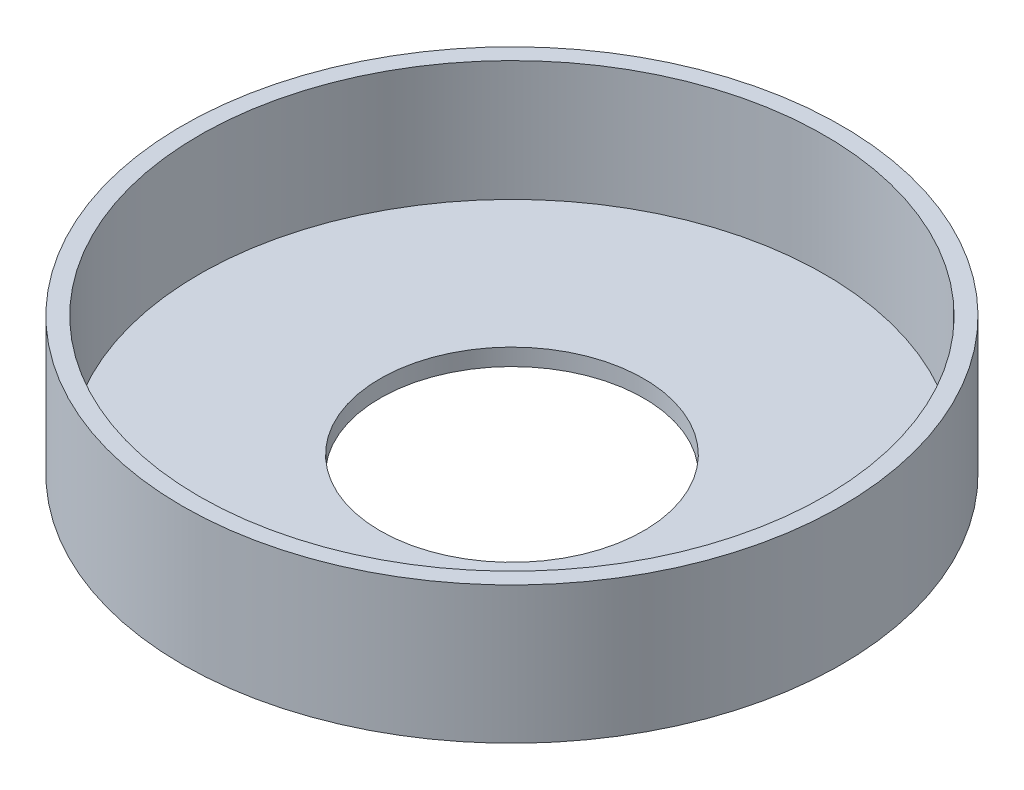
SolidWorks part; units mm, degrees
material "ABS"
ref_plane "Front Plane" through (0, 0, 0) normal (0, 0, 1) x (1, 0, 0)
ref_plane "Top Plane" through (0, 0, 0) normal (0, 1, 0) x (1, 0, 0)
ref_plane "Right Plane" through (0, 0, 0) normal (1, 0, 0) x (0, 0, -1)
sketch "Sketch1" plane through (0, 0, 0) normal (0, 1, 0) x (1, 0, 0)
  circle A0 centre (0, 0) radius 12.5
  circle A1 centre (0, 0) radius 31.25
  dimension "D1" = 62.5
  dimension "D2" = 25
extrude "Boss-Extrude1" add sketch "Sketch1" along normal blind 1.6
sketch "Sketch2" plane through (0, 1.6, 0) normal (0, 1, 0) x (1, 0, 0)
  circle A0 centre (0, 0) radius 31.25 construction
  circle A1 centre (0, 0) radius 31.25
  circle A2 centre (0, 0) radius 29.65
  dimension "D1" = 1.6
extrude "Boss-Extrude2" add sketch "Sketch2" along normal blind 11.4
